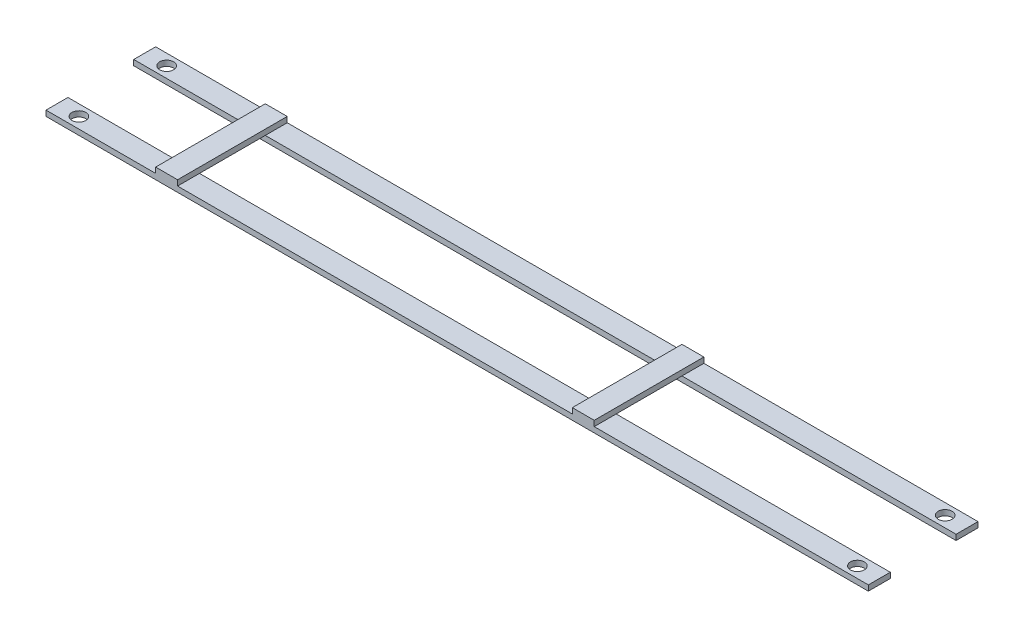
SolidWorks part; units mm, degrees
ref_plane "Front Plane" through (0, 0, 0) normal (0, 0, 1) x (1, 0, 0)
ref_plane "Top Plane" through (0, 0, 0) normal (0, 1, 0) x (1, 0, 0)
ref_plane "Right Plane" through (0, 0, 0) normal (1, 0, 0) x (0, 0, -1)
sketch "Sketch1" plane through (0, 0, 0) normal (0, 1, 0) x (1, 0, 0)
  line L1 (0, 0) -> (1200, 0)
  line L2 (0, 0) -> (0, -40)
  line L3 (0, -40) -> (1200, -40)
  line L4 (1200, 0) -> (1200, -40)
  dimension "D1" = 40
  dimension "D2" = 1200
extrude "Boss-Extrude1" add sketch "Sketch1" along normal blind 10
sketch "Sketch2" plane through (0, 10, 0) normal (0, 1, 0) x (1, 0, 0)
  line L0 (0, -40) -> (1200, -40) construction
  line L1 (240, -40) -> (200, -40)
  line L2 (240, -40) -> (240, 160)
  line L3 (240, 160) -> (200, 160)
  line L4 (200, -40) -> (200, 160)
  line L6 (0, 0) -> (0, -40) construction
  line L7 (1200, -40) -> (1200, 0) construction
  line L8 (1000, -40) -> (960, -40)
  line L9 (1000, -40) -> (1000, 160)
  line L10 (1000, 160) -> (960, 160)
  line L11 (960, -40) -> (960, 160)
  dimension "D1" = 200
  dimension "D2" = 40
  dimension "D3" = 200
  dimension "D4" = 200
  dimension "D5" = 40
  dimension "D6" = 200
extrude "Boss-Extrude2" add sketch "Sketch2" along normal blind 10
sketch "Sketch3" plane through (0, 10, 0) normal (0, -1, 0) x (1, 0, 0)
  line L0 (1200, 0) -> (0, 0) construction
  line L1 (0, -160) -> (1200, -160)
  line L2 (0, -160) -> (0, -120)
  line L3 (0, -120) -> (1200, -120)
  line L4 (1200, -160) -> (1200, -120)
  line L5 (0, 0) -> (0, 40) construction
  dimension "D1" = 40
  dimension "D2" = 1200
  dimension "D3" = 120
  dimension "D4" = 0
extrude "Boss-Extrude3" add sketch "Sketch3" along normal blind 10
sketch "Sketch5" plane through (0, 10, 0) normal (0, 1, 0) x (1, 0, 0)
  line L4 (-809.9506, -40) -> (-809.9506, 0)
  line L9 (1200, 160) -> (1500, 160)
  line L10 (1200, 160) -> (1200, 120)
  line L11 (1200, 120) -> (1500, 120)
  line L12 (1500, 160) -> (1500, 120)
  line L13 (1200, 0) -> (1500, 0)
  line L14 (1200, 0) -> (1200, -40)
  line L15 (1200, -40) -> (1500, -40)
  line L16 (1500, 0) -> (1500, -40)
  dimension "D1" = 300
  dimension "D2" = 300
extrude "Boss-Extrude4" add sketch "Sketch5" against normal up to surface (10 mm away) contours L12 L9 L10 L11 | L16 L13 L14 L15 up to face at (600, 0, -140)
sketch "Sketch4" plane through (0, 0, 0) normal (0, -1, 0) x (1, 0, 0)
  line L1 (1500, 0) -> (0, 0) construction
  line L3 (1500, -120) -> (0, -120) construction
  line L4 (0, 40) -> (1500, 40) construction
  line L5 (0, 0) -> (0, 40) construction
  line L6 (0, -120) -> (0, -160) construction
  line L7 (0, 0) -> (1367.11, 0) construction
  line L8 (1500, 40) -> (1500, 0) construction
  line L9 (1500, -120) -> (1500, -160) construction
  circle A0 centre (1460, 20) radius 12.7
  circle A1 centre (40, 20) radius 12.7
  circle A2 centre (40, -140) radius 12.7
  circle A3 centre (1460, -140) radius 12.7
  dimension "D1" = 25.4
  dimension "D2" = 25.4
  dimension "D3" = 25.4
  dimension "D4" = 25.4
  dimension "D7" = 40
  dimension "D9" = 20
  dimension "D10" = 40
  dimension "D11" = 20
  dimension "D12" = 40
  dimension "D5" = 40
  dimension "D6" = 20
  dimension "D8" = 20
  dimension "D13" = 20
  dimension "D14" = 40
extrude "Cut-Extrude1" cut sketch "Sketch4" against normal blind 10
